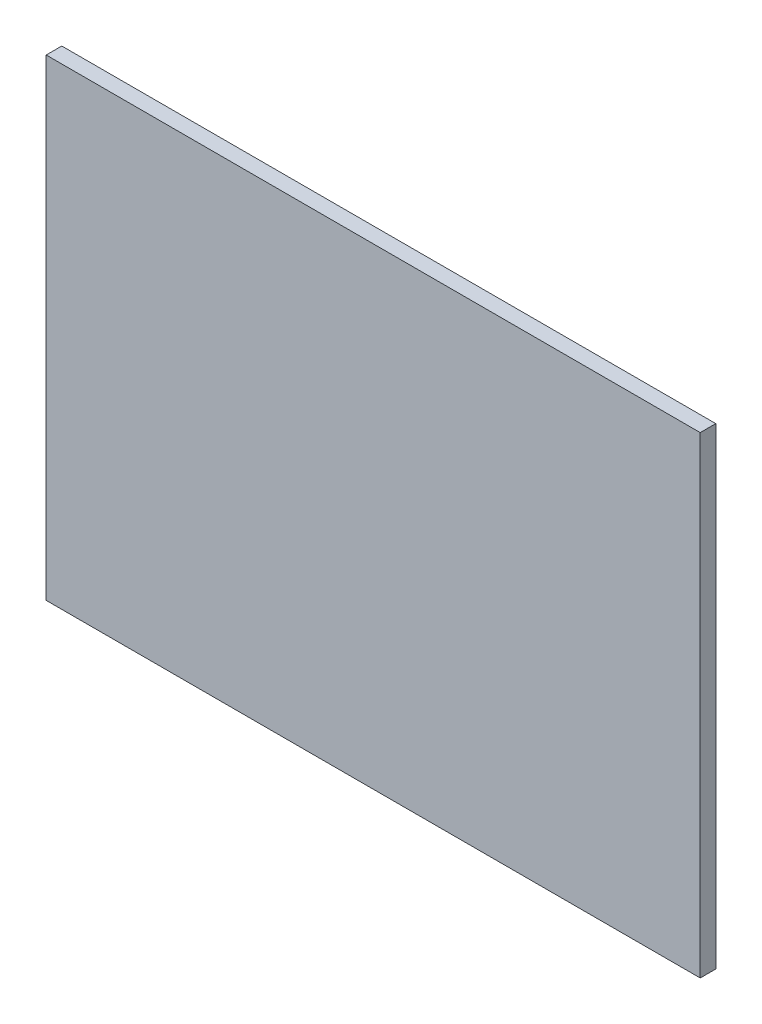
SolidWorks part; units mm, degrees
ref_plane "前视基准面" through (0, 0, 0) normal (0, 0, 1) x (1, 0, 0)
ref_plane "上视基准面" through (0, 0, 0) normal (0, 1, 0) x (1, 0, 0)
ref_plane "右视基准面" through (0, 0, 0) normal (1, 0, 0) x (0, 0, -1)
sketch "草图1" plane through (0, 0, 0) normal (0, 0, 1) x (1, 0, 0)
  line L0 (-58.8948, 0) -> (74.6601, 0) construction
  line L1 (-63, 45.5) -> (63, 45.5)
  line L2 (-63, 45.5) -> (-63, -45.5)
  line L3 (-63, -45.5) -> (63, -45.5)
  line L4 (63, 45.5) -> (63, -45.5)
  line L5 (0, 46.2468) -> (0, -45.6426) construction
  dimension "D1" = 126
  dimension "D2" = 91
extrude "凸台-拉伸1" add sketch "草图1" along normal blind 3
